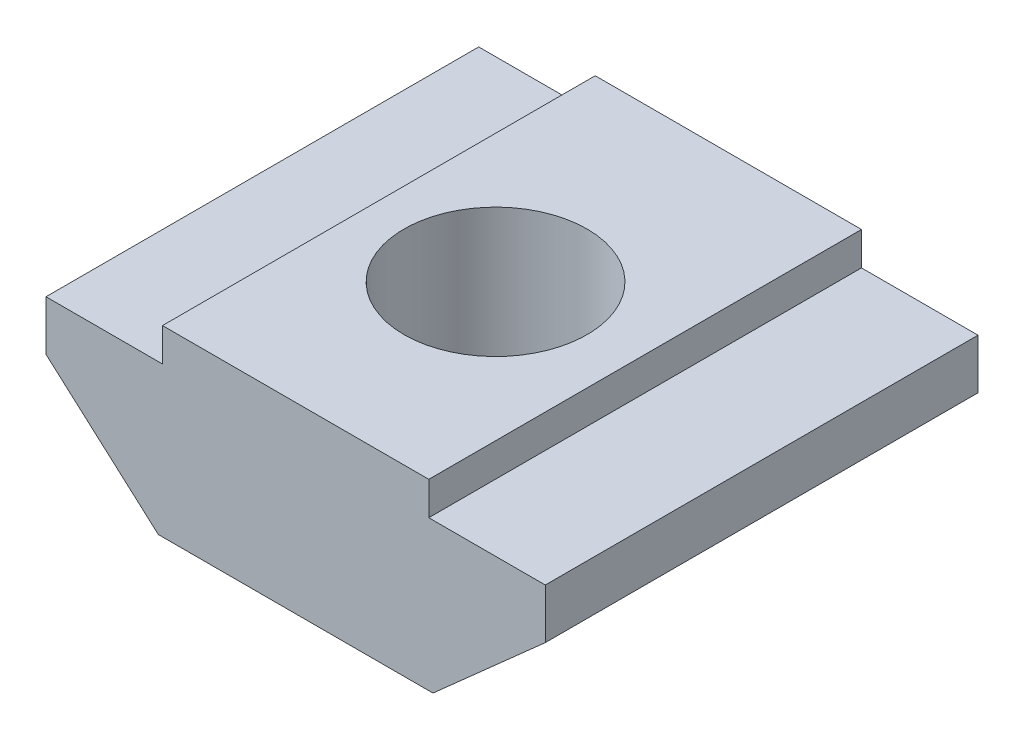
SolidWorks part; units mm, degrees
ref_plane "Спереди" through (0, 0, 0) normal (0, 0, 1) x (1, 0, 0)
ref_plane "Сверху" through (0, 0, 0) normal (0, 1, 0) x (1, 0, 0)
ref_plane "Справа" through (0, 0, 0) normal (1, 0, 0) x (0, 0, -1)
sketch "Эскиз1" plane through (0, 0, 0) normal (0, 0, 1) x (1, 0, 0)
  line L0 (-4.4619, 0) -> (3.7881, 0)
  line L2 (-4.4619, 0) -> (-7.8369, 3)
  line L3 (-7.8369, 3) -> (-7.8369, 4.5)
  line L4 (-7.8369, 4.5) -> (-4.3369, 4.5)
  line L5 (-4.3369, 4.5) -> (-4.3369, 5.5)
  line L6 (-4.3369, 5.5) -> (3.6631, 5.5)
  line L7 (3.6631, 5.5) -> (3.6631, 4.5)
  line L8 (3.6631, 4.5) -> (7.1631, 4.5)
  line L9 (7.1631, 4.5) -> (7.1631, 3)
  line L11 (3.7881, 0) -> (7.1631, 3)
  point P2 (-0.9835, -0.1109)
  point P3 (-0.9835, 0)
  dimension "D1" = 8
  dimension "D2" = 8.25
  dimension "D3" = 1
  dimension "D4" = 15
  dimension "D5" = 1.5
  dimension "D6" = 5.5
  dimension "D7" = 0
  dimension "D8" = 3.6631
  dimension "D11" = 0.9835
extrude "Бобышка-Вытянуть1" add sketch "Эскиз1" along normal blind 13
hole_wizard "Зенковка для  винта с плоской головкой M52" positions "Трехмерный эскиз1" profile "Эскиз4" countersink size "M5" standard "Ansi Metric" end condition through all
sketch3d "Трехмерный эскиз1"
  point P1 (-0.4718, 5.5, 6.8592)
sketch "Эскиз4" plane through (-0.4718, 5.5, 6.8592) normal (1, 0, 0) x (0, 0, 1)
  line L0 (0, 0) -> (0, 5.5)
  line L1 (0, 5.5) -> (2.75, 5.5)
  line L2 (2.75, 5.5) -> (2.75, 2.45)
  line L3 (2.75, 2.45) -> (2.75, 0)
  line L5 (2.75, 0) -> (0, 0)
  line L6 (-2.75, 2.45) -> (-2.75, 0) construction
  line L11 (0, -6.35) -> (0, 107.95) construction
  dimension "Диаметр сквозного отверстия" = 5.5
  dimension "Глубина сквозного отверстия" = 5.5
  dimension "Диаметр передней зенковки" = 5.5
